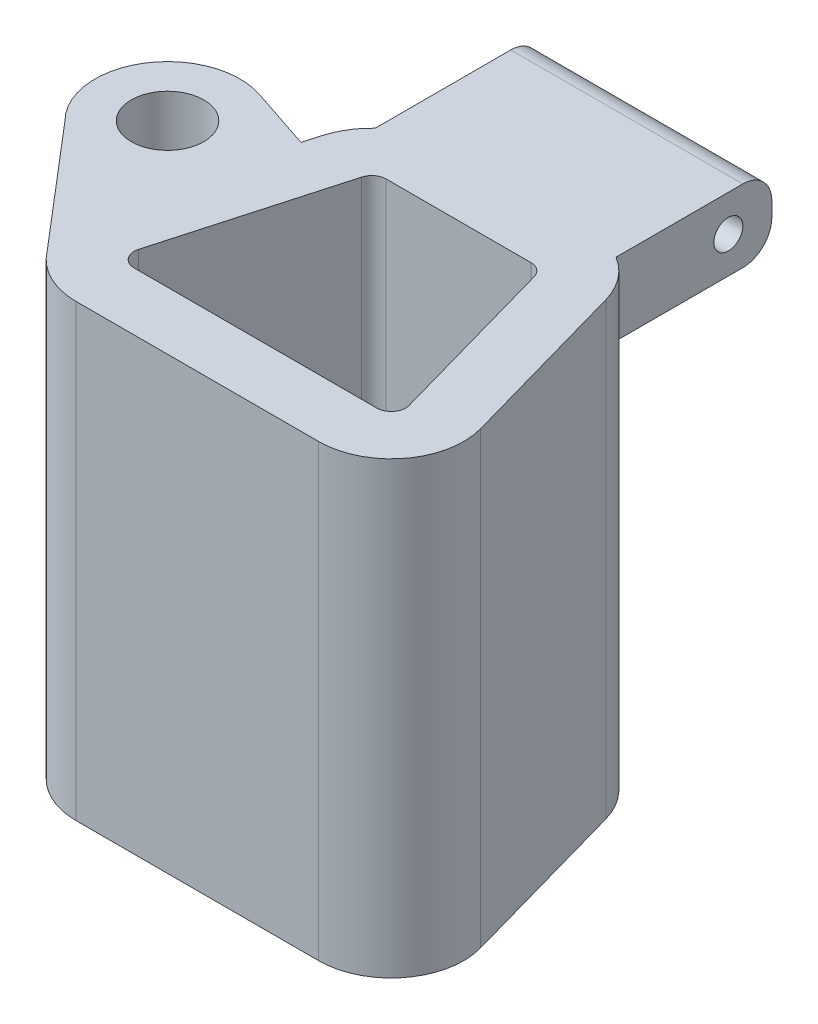
SolidWorks part; units mm, degrees
ref_plane "Front Plane" through (0, 0, 0) normal (0, 0, 1) x (1, 0, 0)
ref_plane "Top Plane" through (0, 0, 0) normal (0, 1, 0) x (1, 0, 0)
ref_plane "Right Plane" through (0, 0, 0) normal (1, 0, 0) x (0, 0, -1)
sketch "Sketch1" plane through (0, 0, 0) normal (0, 1, 0) x (1, 0, 0)
  line L8 (-8.3599, -11) -> (8.3599, -11)
  line L9 (9.7982, 7.3537) -> (13.1732, -4.6463)
  line L10 (-4.9849, 11) -> (4.9849, 11)
  line L11 (-9.7982, 7.3537) -> (-13.1732, -4.6463)
  line L12 (5.9476, 6.2707) -> (9.3226, -5.7293)
  line L13 (-4.9849, 7) -> (4.9849, 7)
  line L14 (-5.9476, 6.2707) -> (-9.3226, -5.7293)
  line L15 (-8.3599, -7) -> (8.3599, -7)
  arc A8 (8.3599, -11) -> (13.1732, -4.6463) centre (8.3599, -6) ccw
  arc A9 (4.9849, 11) -> (9.7982, 7.3537) centre (4.9849, 6) cw
  arc A10 (-4.9849, 11) -> (-9.7982, 7.3537) centre (-4.9849, 6) ccw
  arc A11 (-8.3599, -11) -> (-13.1732, -4.6463) centre (-8.3599, -6) cw
  arc A12 (8.3599, -7) -> (9.3226, -5.7293) centre (8.3599, -6) ccw
  arc A13 (4.9849, 7) -> (5.9476, 6.2707) centre (4.9849, 6) cw
  arc A14 (-4.9849, 7) -> (-5.9476, 6.2707) centre (-4.9849, 6) ccw
  arc A15 (-8.3599, -7) -> (-9.3226, -5.7293) centre (-8.3599, -6) cw
  point P11 (11, -8)
  point P14 (-11, -8)
  point P17 (-6.5, 8)
  point P20 (6.5, 8)
  dimension "D1" = 22
  dimension "D3" = 13
extrude "Boss-Extrude1" add sketch "Sketch1" along normal blind 31
sketch "Sketch2" plane through (0, 0, -11) normal (0, 0, -1) x (-1, 0, 0)
  line L0 (9.7982, 31) -> (4.9849, 31) construction
  line L1 (-7.6014, 26) -> (8.3986, 26)
  line L2 (-7.6014, 26) -> (-7.6014, 31)
  line L3 (-7.6014, 31) -> (8.3986, 31)
  line L4 (8.3986, 26) -> (8.3986, 31)
  line L5 (-7.6014, 26) -> (8.3986, 31) construction
  line L6 (-7.6014, 31) -> (8.3986, 26) construction
  point P0 (0.3986, 28.5)
  dimension "D1" = 16
  dimension "D2" = 5
  dimension "D3" = 2.5
extrude "Boss-Extrude2" add sketch "Sketch2" along normal blind 10 and the other way up to surface other way up to face at (0, 15.5, -7)
sketch "Sketch3" plane through (-8.3986, 0, 0) normal (-1, 0, 0) x (0, 0, 1)
  line L0 (-9.6533, 31) -> (-21, 31) construction
  line L1 (-21, 26) -> (-21, 31) construction
  circle A0 centre (-18, 28.5) radius 1
  dimension "D1" = 2
  dimension "D2" = 2.5
  dimension "D3" = 3
extrude "Cut-Extrude1" cut sketch "Sketch3" against normal through all
fillet "Fillet1" radius 2 2 edges at (-0.3986, 26, -21) (-0.3986, 31, -21)
sketch "Sketch4" plane through (0, 31, 0) normal (0, 1, 0) x (1, 0, 0)
  line L0 (-19.5355, -0.5966) -> (-12.3454, -9.0192)
  line L1 (-14.4209, 7.683) -> (-10.1092, 6.2478)
  line L2 (-9.7982, 7.3537) -> (-13.1732, -4.6463) construction
  line L3 (-12.3454, -9.0192) -> (-10.1092, 6.2478)
  arc A0 (-14.4209, 7.683) -> (-19.5355, -0.5966) centre (-16, 2.9389) ccw
  circle A1 centre (-16, 2.9389) radius 2.5
  arc A2 (-13.1732, -4.6463) -> (-8.3599, -11) centre (-8.3599, -6) ccw construction
  dimension "D1" = 10
  dimension "D2" = 5
  dimension "D3" = 16
extrude "Boss-Extrude3" add sketch "Sketch4" against normal through all
sketch "Sketch6" plane through (0.8639, 0, -2.5953) normal (0.3158, 0, -0.9488) x (-0.9488, 0, -0.3158)
  line L0 (21.1093, 0) -> (21.1093, 31) construction
  line L1 (30.5938, 6.75) -> (11.6247, 6.75)
  line L2 (30.5938, 6.75) -> (30.5938, 24.25)
  line L3 (30.5938, 24.25) -> (11.6247, 24.25)
  line L4 (11.6247, 6.75) -> (11.6247, 24.25)
  line L5 (30.5938, 6.75) -> (11.6247, 24.25) construction
  line L6 (30.5938, 24.25) -> (11.6247, 6.75) construction
  line L7 (11.6247, 0) -> (11.6247, 31) construction
  point P0 (21.1093, 15.5)
  dimension "D1" = 17.5
extrude "Cut-Extrude2" cut sketch "Sketch6" against normal through all
